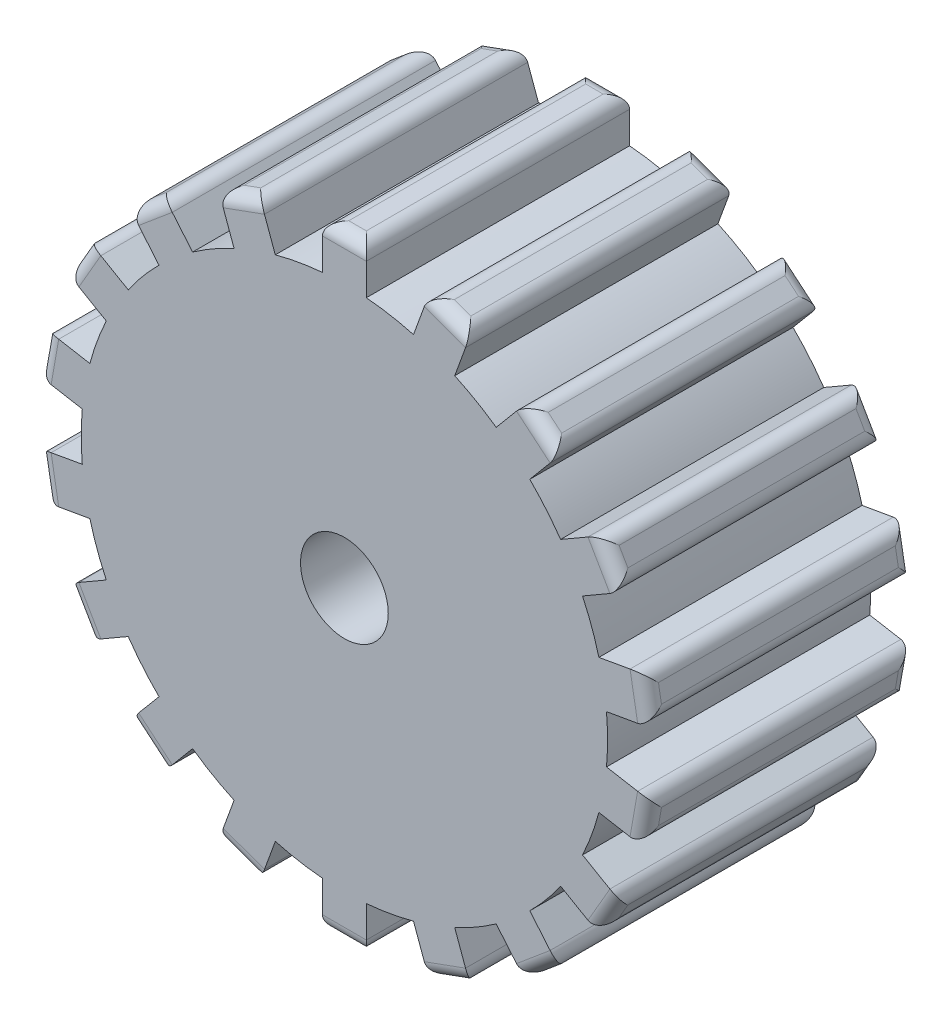
SolidWorks part; units mm, degrees
ref_plane "Front Plane" through (0, 0, 0) normal (0, 0, 1) x (1, 0, 0)
ref_plane "Top Plane" through (0, 0, 0) normal (0, 1, 0) x (1, 0, 0)
ref_plane "Right Plane" through (0, 0, 0) normal (1, 0, 0) x (0, 0, -1)
sketch "Sketch2" plane through (0, 0, 0) normal (0, 0, 1) x (1, 0, 0)
  circle A0 centre (0, 0) radius 60
extrude "Boss-Extrude1" add sketch "Sketch2" along normal blind 60
sketch "Sketch3" plane through (0, 0, 60) normal (0, 0, 1) x (1, 0, 0)
  line L0 (0, 60) -> (0, 70) construction
  line L1 (5, 70) -> (-5, 70)
  line L2 (-5, 70) -> (-5, 59.5215)
  line L3 (-5, 59.5215) -> (5, 59.5215)
  line L4 (5, 59.5215) -> (5, 70)
  circle A0 centre (0, 0) radius 60 construction
  point P9 (0, 70)
extrude "Boss-Extrude2" add sketch "Sketch3" against normal blind 60
fillet "Fillet2" radius 3 4 edges at (-5, 70, 30) (0, 70, 60) (0, 70, 0) (5, 70, 30)
pattern_circular "CirPattern1" count 18 over 360 about axis through (0, 0, 0) along (0, 0, 1) of "Fillet2", "Boss-Extrude2"
sketch "Sketch4" plane through (0, 0, 60) normal (0, 0, 1) x (1, 0, 0)
  circle A0 centre (0, 0) radius 10
extrude "Cut-Extrude1" cut sketch "Sketch4" against normal blind 60
